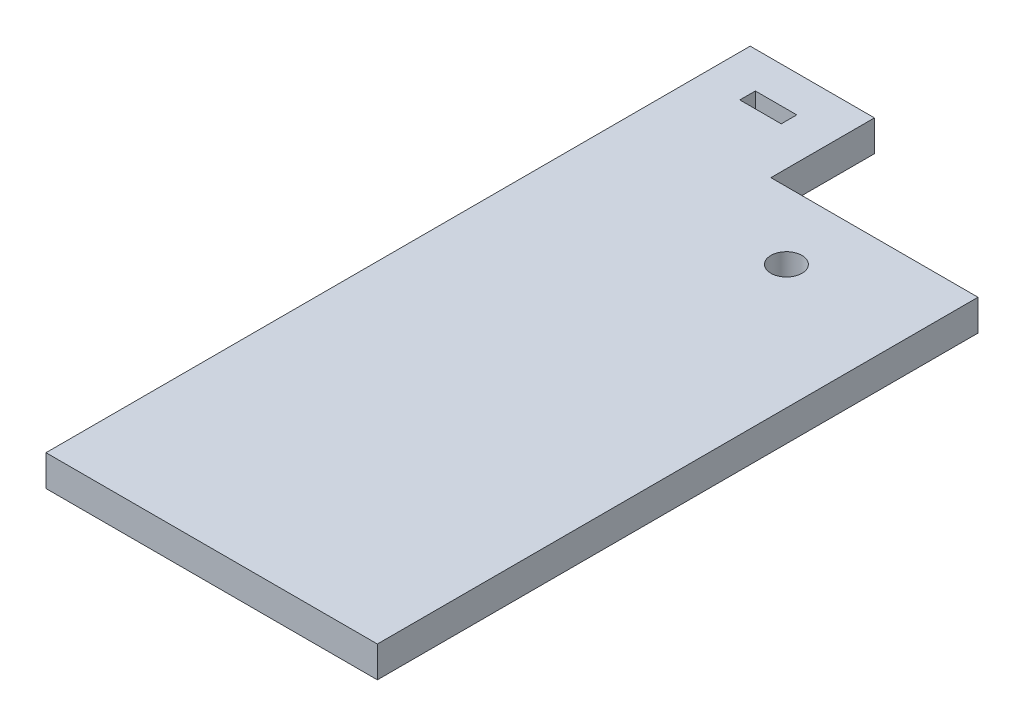
SolidWorks part; units mm, degrees
ref_plane "Front Plane" through (0, 0, 0) normal (0, 0, 1) x (1, 0, 0)
ref_plane "Top Plane" through (0, 0, 0) normal (0, 1, 0) x (1, 0, 0)
ref_plane "Right Plane" through (0, 0, 0) normal (1, 0, 0) x (0, 0, -1)
sketch "Sketch1" plane through (0, 0, 0) normal (0, 1, 0) x (1, 0, 0)
  line L0 (0, 58) -> (0, 68)
  line L1 (0, 0) -> (44, 0)
  line L2 (0, 0) -> (0, 58)
  line L4 (44, 0) -> (44, 58)
  line L5 (0, 68) -> (12, 68)
  line L7 (12, 68) -> (12, 58)
  line L8 (12, 58) -> (44, 58)
  line L9 (20, 51.5) -> (36, 51.5) construction
  line L10 (4, 64.5) -> (8, 64.5)
  line L11 (4, 64.5) -> (4, 63)
  line L12 (4, 63) -> (8, 63)
  line L13 (8, 64.5) -> (8, 63)
  circle A0 centre (20, 51.5) radius 1.5
  circle A1 centre (36, 51.5) radius 1.5
  point P12 (28, 51.5)
  point P13 (28, 58)
  dimension "D5" = 3
  dimension "D6" = 3
  dimension "D1" = 44
  dimension "D2" = 58
  dimension "D3" = 10
  dimension "D4" = 12
  dimension "D7" = 16
  dimension "D8" = 6.5
  dimension "D9" = 1.5
  dimension "D10" = 4
  dimension "D11" = 5
  dimension "D12" = 4
extrude "Boss-Extrude1" add sketch "Sketch1" along normal blind 3
sketch "Sketch3" plane through (0, 0, 0) normal (0, 0, 1) x (1, 0, 0)
  line L0 (0, 3) -> (44, 3) construction
  line L1 (44, 0) -> (32, 0)
  line L2 (44, 0) -> (44, 3)
  line L3 (44, 3) -> (32, 3)
  line L4 (32, 0) -> (32, 3)
  dimension "D1" = 12
extrude "Cut-Extrude2" cut sketch "Sketch3" against normal through all
